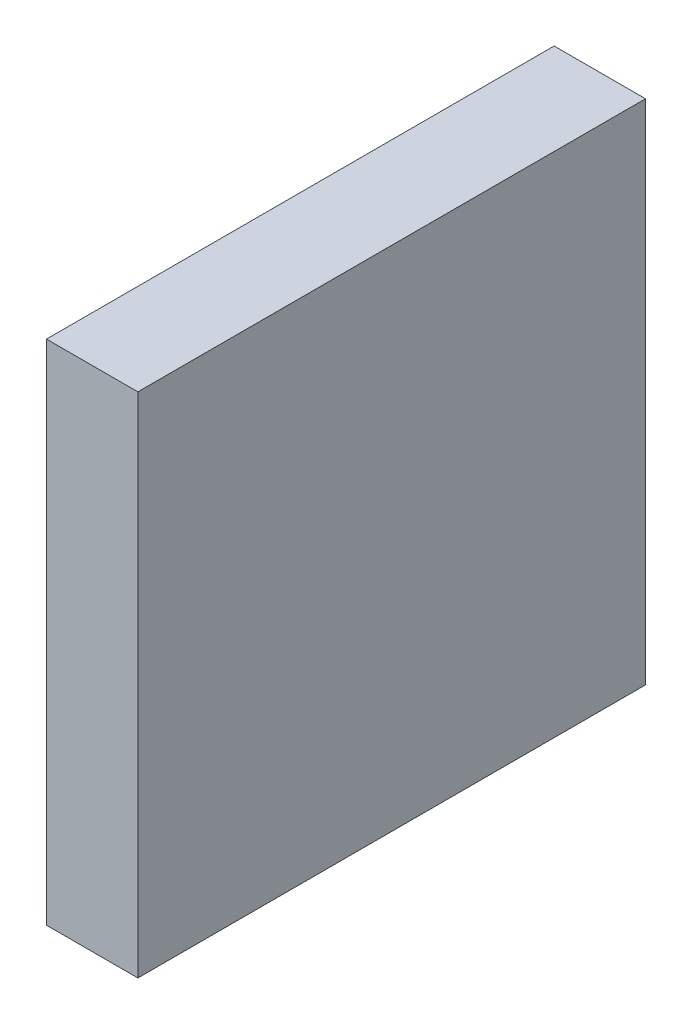
SolidWorks part; units mm, degrees
material "Perspex (TM) GS Acrylic Cast Sheet"
ref_plane "Front Plane" through (0, 0, 0) normal (0, 0, 1) x (1, 0, 0)
ref_plane "Top Plane" through (0, 0, 0) normal (0, 1, 0) x (1, 0, 0)
ref_plane "Right Plane" through (0, 0, 0) normal (1, 0, 0) x (0, 0, -1)
sketch "Sketch1" plane through (0, 0, 0) normal (1, 0, 0) x (0, 0, -1)
  line L1 (-12.5, -12.5) -> (12.5, -12.5)
  line L2 (-12.5, -12.5) -> (-12.5, 12.5)
  line L3 (-12.5, 12.5) -> (12.5, 12.5)
  line L4 (12.5, -12.5) -> (12.5, 12.5)
  line L5 (-12.5, -12.5) -> (12.5, 12.5) construction
  line L6 (-12.5, 12.5) -> (12.5, -12.5) construction
  point P0 (0, 0)
  point P6 (0, 0)
  dimension "D1" = 25
extrude "Boss-Extrude1" add sketch "Sketch1" along normal blind 4.5
sketch "Sketch2" plane through (4.5, 0, 0) normal (1, 0, 0) x (0, 0, -1)
  circle A0 centre (0, 0) radius 3.125
  dimension "D1" = 6.25
sketch "Sketch3" plane through (0, 0, 0) normal (-1, 0, 0) x (0, 0, 1)
  circle A0 centre (0, 0) radius 3.125
